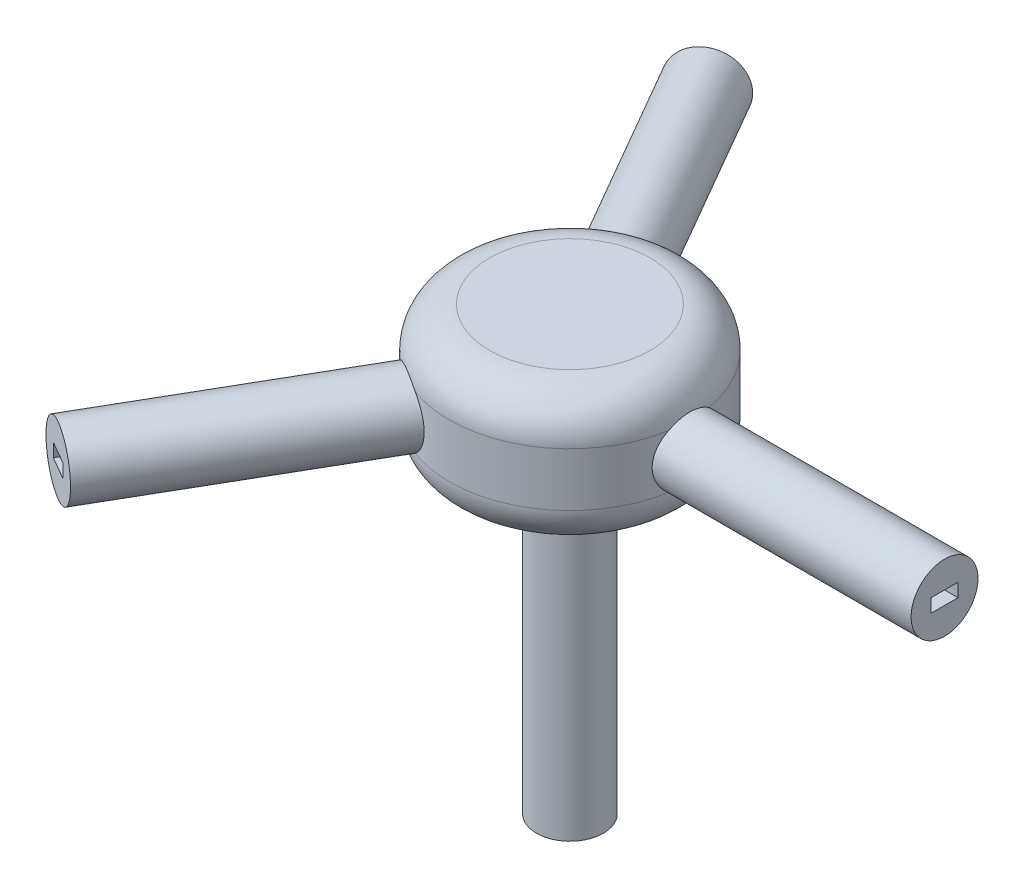
SolidWorks part; units mm, degrees
ref_plane "前视基准面" through (0, 0, 0) normal (0, 0, 1) x (1, 0, 0)
ref_plane "上视基准面" through (0, 0, 0) normal (0, 1, 0) x (1, 0, 0)
ref_plane "右视基准面" through (0, 0, 0) normal (1, 0, 0) x (0, 0, -1)
sketch "草图1" plane through (0, 0, 0) normal (0, 0, 1) x (1, 0, 0)
  line L0 (0, 124) -> (0, -129.3333) construction
  line L1 (-134.6667, 0) -> (82, 0) construction
  line L2 (0, -50) -> (60, -50)
  line L3 (0, -50) -> (0, 50)
  line L4 (0, 50) -> (60, 50)
  line L5 (90, -20) -> (90, 20)
  line L7 (0, -50) -> (25, -50)
  line L8 (0, -50) -> (0, -280)
  line L9 (0, -280) -> (25, -280)
  line L10 (25, -50) -> (25, -280)
  arc A0 (90, -20) -> (60, -50) centre (60, -20) cw
  arc A1 (90, 20) -> (60, 50) centre (60, 20) ccw
  point P10 (-26.3333, 0)
  point P15 (90, 50)
  dimension "D4" = 30
  dimension "D1" = 50
  dimension "D2" = 50
  dimension "D3" = 90
  dimension "D5" = 230
  dimension "D6" = 25
revolve "旋转1" add sketch "草图1" angle 360 about L0
sketch "草图3" plane through (0, 0, 0) normal (0, 0, 1) x (1, 0, 0)
  line L0 (0, 0) -> (148.2659, 0) construction
sketch "草图5" plane through (0, 0, 0) normal (1, 0, 0) x (0, 0, -1)
  circle A0 centre (0, 0) radius 25
extrude "凸台-拉伸1" add sketch "草图5" along normal blind 280
pattern_circular "阵列(圆周)1" count 3 over 360 about axis through (0, 0, 0) along (0, 1, 0) of "凸台-拉伸1"
sketch "草图7" plane through (280, 0, 0) normal (1, 0, 0) x (0, 0, -1)
  line L1 (-10, -5) -> (10, -5)
  line L2 (-10, -5) -> (-10, 5)
  line L3 (-10, 5) -> (10, 5)
  line L4 (10, -5) -> (10, 5)
  line L5 (-10, -5) -> (10, 5) construction
  line L6 (-10, 5) -> (10, -5) construction
  point P0 (0, 0)
  dimension "D1" = 10
  dimension "D2" = 20
extrude "切除-拉伸2" cut sketch "草图7" against normal blind 10
pattern_circular "阵列(圆周)2" count 3 over 360 about axis through (0, 0, 0) along (0, 1, 0) of "切除-拉伸2"
